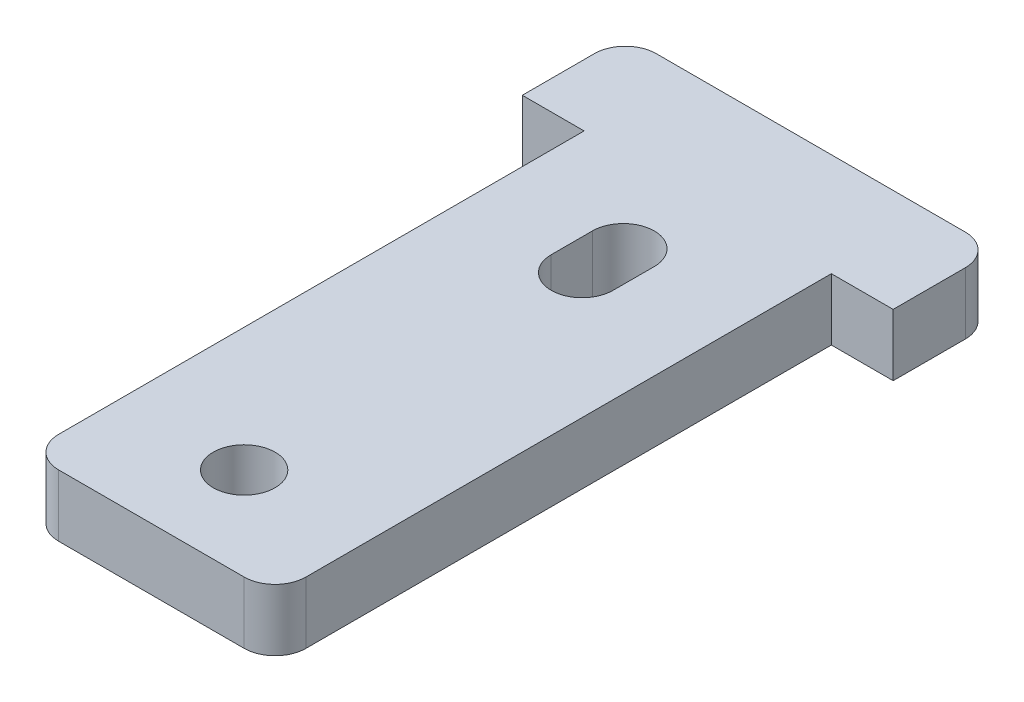
SolidWorks part; units mm, degrees
ref_plane "Plan de face" through (0, 0, 0) normal (0, 0, 1) x (1, 0, 0)
ref_plane "Plan de dessus" through (0, 0, 0) normal (0, 1, 0) x (1, 0, 0)
ref_plane "Plan de droite" through (0, 0, 0) normal (1, 0, 0) x (0, 0, -1)
sketch "Esquisse1" plane through (0, 0, 0) normal (0, 1, 0) x (1, 0, 0)
  line L1 (0, 0) -> (18, 0)
  line L2 (0, 0) -> (0, 32)
  line L3 (0, 32) -> (18, 32)
  line L4 (18, 0) -> (18, 32)
  dimension "D1" = 18
  dimension "D2" = 32
extrude "Boss.-Extru.1" add sketch "Esquisse1" along normal blind 3
sketch "Esquisse2" plane through (0, 3, 0) normal (0, 1, 0) x (1, 0, 0)
  line L1 (0, 0) -> (3, 0)
  line L2 (0, 0) -> (0, 27)
  line L3 (0, 27) -> (3, 27)
  line L4 (3, 0) -> (3, 27)
  dimension "D1" = 3
  dimension "D2" = 27
extrude "Enlèv. mat.-Extru.1" cut sketch "Esquisse2" against normal up to next
sketch "Esquisse3" plane through (0, 3, 0) normal (0, 1, 0) x (1, 0, 0)
  line L1 (18, 0) -> (15, 0)
  line L2 (18, 0) -> (18, 27)
  line L3 (18, 27) -> (15, 27)
  line L4 (15, 0) -> (15, 27)
  dimension "D1" = 27
  dimension "D2" = 3
extrude "Enlèv. mat.-Extru.2" cut sketch "Esquisse3" against normal up to next
sketch "Esquisse4" plane through (0, 3, 0) normal (0, 1, 0) x (1, 0, 0)
  line L0 (18, 32) -> (0, 32) construction
  line L1 (3, 0) -> (3, 27) construction
  circle A0 centre (9, 4.5) radius 1.5
  dimension "D1" = 3
  dimension "D2" = 27.5
  dimension "D3" = 6
extrude "Enlèv. mat.-Extru.3" cut sketch "Esquisse4" against normal up to next contours A0
fillet "Congé1" radius 1.5 2 edges at (18, 1.5, -32) (0, 1.5, -32)
fillet "Congé2" radius 1.5 2 edges at (15, 1.5, 0) (3, 1.5, 0)
sketch "Esquisse5" plane through (0, 3, 0) normal (0, 1, 0) x (1, 0, 0)
  line L0 (8.9036, 23) -> (8.9036, 21) construction
  line L1 (10.4036, 23) -> (10.4036, 21)
  line L2 (7.4036, 23) -> (7.4036, 21)
  line L3 (16.5, 32) -> (1.5, 32) construction
  arc A0 (10.4036, 23) -> (7.4036, 23) centre (8.9036, 23) ccw
  arc A1 (7.4036, 21) -> (10.4036, 21) centre (8.9036, 21) ccw
  point P2 (8.9036, 22)
  dimension "D1" = 3
  dimension "D2" = 2
  dimension "D3" = 9
extrude "Enlèv. mat.-Extru.4" cut sketch "Esquisse5" against normal up to next contours A0 L2 A1 L1
